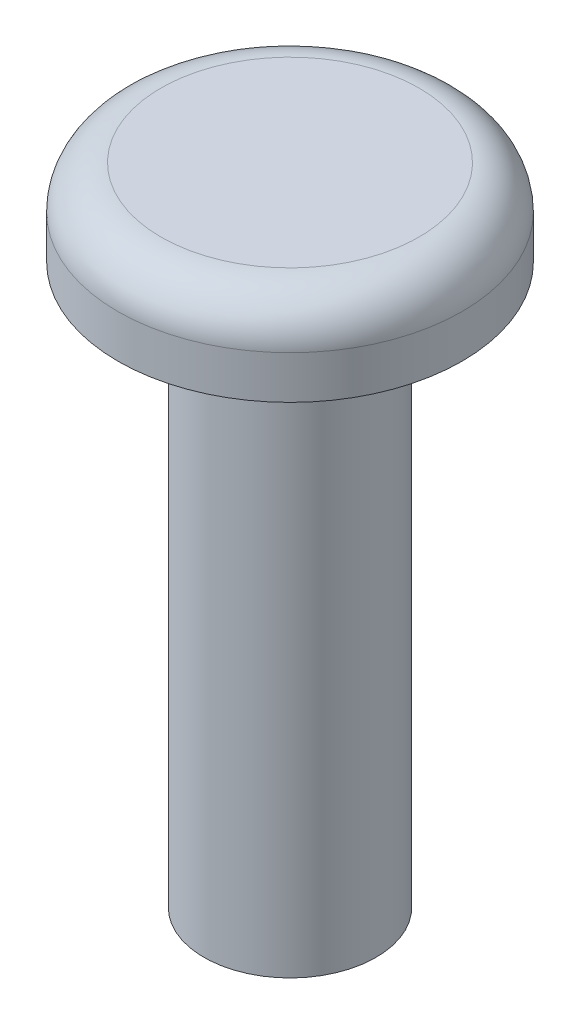
SolidWorks part; units mm, degrees
ref_plane "Front Plane" through (0, 0, 0) normal (0, 0, 1) x (1, 0, 0)
ref_plane "Top Plane" through (0, 0, 0) normal (0, 1, 0) x (1, 0, 0)
ref_plane "Right Plane" through (0, 0, 0) normal (1, 0, 0) x (0, 0, -1)
sketch "Sketch1" plane through (0, 0, 0) normal (0, 1, 0) x (1, 0, 0)
  circle A0 centre (0, 0) radius 20
  dimension "D1" = 40
extrude "Boss-Extrude1" add sketch "Sketch1" along normal blind 10
sketch "Sketch2" plane through (0, 0, 0) normal (0, -1, 0) x (1, 0, 0)
  circle A0 centre (0, 0) radius 10
  dimension "D1" = 20
extrude "Boss-Extrude2" add sketch "Sketch2" along normal blind 65
fillet "Fillet1" radius 5 1 edges at (0, 10, 20)
